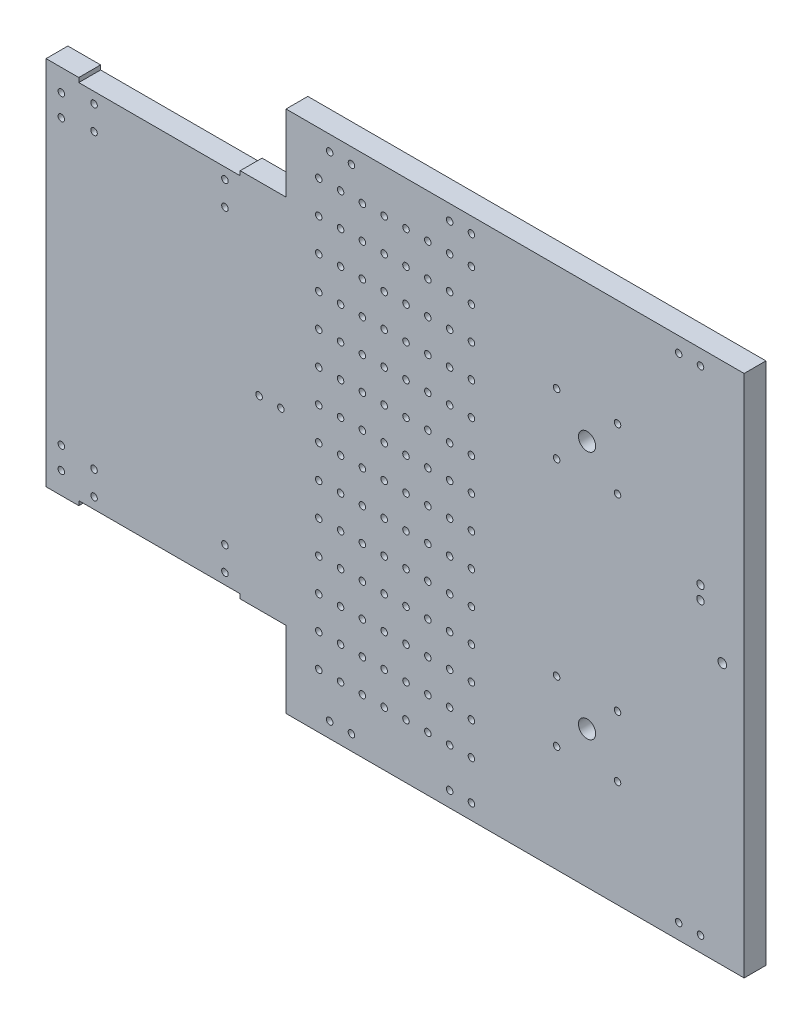
SolidWorks part; units mm, degrees
ref_plane "Front Plane" through (0, 0, 0) normal (0, 0, 1) x (1, 0, 0)
ref_plane "Top Plane" through (0, 0, 0) normal (0, 1, 0) x (1, 0, 0)
ref_plane "Right Plane" through (0, 0, 0) normal (1, 0, 0) x (0, 0, -1)
sketch "Sketch1" plane through (0, 0, 0) normal (0, 0, 1) x (1, 0, 0)
  line L0 (-89.4613, 46.5825) -> (-89.4613, 11.5825)
  line L1 (-89.4613, 46.5825) -> (120.5387, 46.5825)
  line L2 (-199.4613, 11.5825) -> (-199.4613, -158.4175)
  line L3 (-89.4613, -193.4175) -> (120.5387, -193.4175)
  line L4 (120.5387, 46.5825) -> (120.5387, -193.4175)
  line L5 (120.5387, -73.4175) -> (-199.4613, -73.4175) construction
  line L6 (-89.4613, -193.4175) -> (-89.4613, -158.4175)
  line L7 (-89.4613, 11.5825) -> (-110.4613, 11.5825)
  line L8 (-89.4613, -158.4175) -> (-110.4613, -158.4175)
  line L9 (-184.4613, 11.5825) -> (-199.4613, 11.5825)
  line L10 (-147.4667, 0.0467) -> (-147.4667, -18.5654) construction
  line L11 (-184.4613, 11.5825) -> (-184.4613, 9.5625)
  line L12 (-184.4613, 9.5625) -> (-110.4613, 9.5625)
  line L13 (-110.4613, 11.5825) -> (-110.4613, 9.5625)
  line L14 (-184.4613, -156.3975) -> (-110.4613, -156.3975)
  line L15 (-184.4613, -158.4175) -> (-184.4613, -156.3975)
  line L16 (-110.4613, -158.4175) -> (-110.4613, -156.3975)
  line L17 (15.5387, 46.5825) -> (15.5387, -193.4175) construction
  line L18 (-184.4613, -158.4175) -> (-199.4613, -158.4175)
  line L19 (31.0387, -16.339) -> (66.0387, -16.339) construction
  line L20 (31.0387, 1.1493) -> (66.0387, 1.1493) construction
  line L21 (31.0387, 1.1493) -> (31.0387, -33.8273) construction
  line L22 (31.0387, -33.8273) -> (66.0387, -33.8273) construction
  line L23 (66.0387, 1.1493) -> (66.0387, -33.8273) construction
  line L24 (31.0387, 1.1493) -> (66.0387, -33.8273) construction
  line L25 (31.0387, -33.8273) -> (66.0387, 1.1493) construction
  line L26 (48.5387, 1.1493) -> (48.5387, -33.8273) construction
  line L27 (48.5387, -147.9844) -> (48.5387, -113.0078) construction
  line L28 (31.0387, -113.0078) -> (66.0387, -147.9844) construction
  line L29 (31.0387, -147.9844) -> (66.0387, -113.0078) construction
  line L30 (66.0387, -147.9844) -> (66.0387, -113.0078) construction
  line L31 (31.0387, -113.0078) -> (66.0387, -113.0078) construction
  line L32 (31.0387, -147.9844) -> (31.0387, -113.0078) construction
  line L33 (31.0387, -147.9844) -> (66.0387, -147.9844) construction
  line L34 (31.0387, -130.4961) -> (66.0387, -130.4961) construction
  line L35 (-91.8179, -73.4175) -> (-101.8179, -73.4175) construction
  line L36 (-36.9613, 46.5825) -> (-36.9613, 37.4665) construction
  circle A0 centre (-177.4613, 4.5825) radius 1.5
  circle A1 centre (-177.4718, -6.4175) radius 1.5
  circle A2 centre (-117.472, 4.5825) radius 1.5
  circle A3 centre (-117.4616, -6.4175) radius 1.5
  circle A4 centre (-177.4718, -6.4175) radius 1.5
  circle A5 centre (-177.4613, 4.5825) radius 1.5
  circle A6 centre (-117.4616, -6.4175) radius 1.5
  circle A7 centre (-117.472, 4.5825) radius 1.5
  circle A8 centre (-177.4613, 4.5825) radius 1.5
  circle A9 centre (-177.4718, -6.4175) radius 1.5
  circle A10 centre (-117.472, 4.5825) radius 1.5
  circle A11 centre (-117.4616, -6.4175) radius 1.5
  circle A12 centre (-177.4718, -6.4175) radius 1.5
  circle A13 centre (-177.4613, 4.5825) radius 1.5
  circle A14 centre (-117.4616, -6.4175) radius 1.5
  circle A15 centre (-117.472, 4.5825) radius 1.5
  circle A16 centre (-177.4613, 4.5825) radius 1.5
  circle A17 centre (-177.4718, -6.4175) radius 1.5
  circle A18 centre (-117.472, 4.5825) radius 1.5
  circle A19 centre (-117.4616, -6.4175) radius 1.5
  circle A20 centre (-177.4718, -6.4175) radius 1.5
  circle A21 centre (-177.4613, 4.5825) radius 1.5
  circle A22 centre (-117.4616, -6.4175) radius 1.5
  circle A23 centre (-117.472, 4.5825) radius 1.5
  circle A24 centre (-177.4613, 4.5825) radius 1.5
  circle A25 centre (-177.4718, -6.4175) radius 1.5
  circle A26 centre (-117.472, 4.5825) radius 1.5
  circle A27 centre (-117.4616, -6.4175) radius 1.5
  circle A28 centre (-177.4718, -6.4175) radius 1.5
  circle A29 centre (-177.4613, 4.5825) radius 1.5
  circle A30 centre (-117.4616, -6.4175) radius 1.5
  circle A31 centre (-117.472, 4.5825) radius 1.5
  circle A32 centre (-117.472, -151.4175) radius 1.5
  circle A33 centre (-117.4616, -140.4175) radius 1.5
  circle A34 centre (-177.4718, -140.4175) radius 1.5
  circle A35 centre (-177.4613, -151.4175) radius 1.5
  circle A36 centre (48.5387, -16.339) radius 3.94
  circle A37 centre (34.5754, -2.385) radius 1.5
  circle A38 centre (62.502, -2.385) radius 1.5
  circle A39 centre (62.502, -30.293) radius 1.5
  circle A40 centre (34.5754, -30.293) radius 1.5
  circle A41 centre (34.5754, -116.5421) radius 1.5
  circle A42 centre (62.502, -116.5421) radius 1.5
  circle A43 centre (62.502, -144.4501) radius 1.5
  circle A44 centre (34.5754, -144.4501) radius 1.5
  circle A45 centre (48.5387, -130.4961) radius 3.94
  circle A46 centre (-74.4613, 26.5825) radius 1.5
  circle A47 centre (100.5387, -186.4175) radius 1.5
  circle A48 centre (90.5387, -186.4175) radius 1.5
  circle A49 centre (-59.4613, -186.4175) radius 1.5
  circle A50 centre (-69.4613, -186.4175) radius 1.5
  circle A51 centre (-69.4613, 39.5825) radius 1.5
  circle A52 centre (-59.4613, 39.5825) radius 1.5
  circle A53 centre (90.5387, 39.5825) radius 1.5
  circle A54 centre (100.5387, 39.5825) radius 1.5
  circle A55 centre (-64.4613, 26.5825) radius 1.5
  circle A56 centre (-54.4613, 26.5825) radius 1.5
  circle A57 centre (-44.4613, 26.5825) radius 1.5
  circle A58 centre (-34.4613, 26.5825) radius 1.5
  circle A59 centre (-24.4613, 26.5825) radius 1.5
  circle A60 centre (-14.4613, 26.5825) radius 1.5
  circle A61 centre (-4.4613, 26.5825) radius 1.5
  circle A62 centre (-64.4613, 11.5825) radius 1.5
  circle A63 centre (-54.4613, 11.5825) radius 1.5
  circle A64 centre (-44.4613, 11.5825) radius 1.5
  circle A65 centre (-34.4613, 11.5825) radius 1.5
  circle A66 centre (-24.4613, 11.5825) radius 1.5
  circle A67 centre (-14.4613, 11.5825) radius 1.5
  circle A68 centre (-4.4613, 11.5825) radius 1.5
  circle A69 centre (-64.4613, -3.4175) radius 1.5
  circle A70 centre (-54.4613, -3.4175) radius 1.5
  circle A71 centre (-44.4613, -3.4175) radius 1.5
  circle A72 centre (-34.4613, -3.4175) radius 1.5
  circle A73 centre (-24.4613, -3.4175) radius 1.5
  circle A74 centre (-14.4613, -3.4175) radius 1.5
  circle A75 centre (-4.4613, -3.4175) radius 1.5
  circle A76 centre (-64.4613, -18.4175) radius 1.5
  circle A77 centre (-54.4613, -18.4175) radius 1.5
  circle A78 centre (-44.4613, -18.4175) radius 1.5
  circle A79 centre (-34.4613, -18.4175) radius 1.5
  circle A80 centre (-24.4613, -18.4175) radius 1.5
  circle A81 centre (-14.4613, -18.4175) radius 1.5
  circle A82 centre (-4.4613, -18.4175) radius 1.5
  circle A83 centre (-64.4613, -33.4175) radius 1.5
  circle A84 centre (-54.4613, -33.4175) radius 1.5
  circle A85 centre (-44.4613, -33.4175) radius 1.5
  circle A86 centre (-34.4613, -33.4175) radius 1.5
  circle A87 centre (-24.4613, -33.4175) radius 1.5
  circle A88 centre (-14.4613, -33.4175) radius 1.5
  circle A89 centre (-4.4613, -33.4175) radius 1.5
  circle A90 centre (-64.4613, -48.4175) radius 1.5
  circle A91 centre (-54.4613, -48.4175) radius 1.5
  circle A92 centre (-44.4613, -48.4175) radius 1.5
  circle A93 centre (-34.4613, -48.4175) radius 1.5
  circle A94 centre (-24.4613, -48.4175) radius 1.5
  circle A95 centre (-14.4613, -48.4175) radius 1.5
  circle A96 centre (-4.4613, -48.4175) radius 1.5
  circle A97 centre (-64.4613, -63.4175) radius 1.5
  circle A98 centre (-54.4613, -63.4175) radius 1.5
  circle A99 centre (-44.4613, -63.4175) radius 1.5
  circle A100 centre (-34.4613, -63.4175) radius 1.5
  circle A101 centre (-24.4613, -63.4175) radius 1.5
  circle A102 centre (-14.4613, -63.4175) radius 1.5
  circle A103 centre (-4.4613, -63.4175) radius 1.5
  circle A104 centre (-64.4613, -78.4175) radius 1.5
  circle A105 centre (-54.4613, -78.4175) radius 1.5
  circle A106 centre (-44.4613, -78.4175) radius 1.5
  circle A107 centre (-34.4613, -78.4175) radius 1.5
  circle A108 centre (-24.4613, -78.4175) radius 1.5
  circle A109 centre (-14.4613, -78.4175) radius 1.5
  circle A110 centre (-4.4613, -78.4175) radius 1.5
  circle A111 centre (-64.4613, -93.4175) radius 1.5
  circle A112 centre (-54.4613, -93.4175) radius 1.5
  circle A113 centre (-44.4613, -93.4175) radius 1.5
  circle A114 centre (-34.4613, -93.4175) radius 1.5
  circle A115 centre (-24.4613, -93.4175) radius 1.5
  circle A116 centre (-14.4613, -93.4175) radius 1.5
  circle A117 centre (-4.4613, -93.4175) radius 1.5
  circle A118 centre (-64.4613, -108.4175) radius 1.5
  circle A119 centre (-54.4613, -108.4175) radius 1.5
  circle A120 centre (-44.4613, -108.4175) radius 1.5
  circle A121 centre (-34.4613, -108.4175) radius 1.5
  circle A122 centre (-24.4613, -108.4175) radius 1.5
  circle A123 centre (-14.4613, -108.4175) radius 1.5
  circle A124 centre (-4.4613, -108.4175) radius 1.5
  circle A125 centre (-64.4613, -123.4175) radius 1.5
  circle A126 centre (-54.4613, -123.4175) radius 1.5
  circle A127 centre (-44.4613, -123.4175) radius 1.5
  circle A128 centre (-34.4613, -123.4175) radius 1.5
  circle A129 centre (-24.4613, -123.4175) radius 1.5
  circle A130 centre (-14.4613, -123.4175) radius 1.5
  circle A131 centre (-4.4613, -123.4175) radius 1.5
  circle A132 centre (-64.4613, -138.4175) radius 1.5
  circle A133 centre (-54.4613, -138.4175) radius 1.5
  circle A134 centre (-44.4613, -138.4175) radius 1.5
  circle A135 centre (-34.4613, -138.4175) radius 1.5
  circle A136 centre (-24.4613, -138.4175) radius 1.5
  circle A137 centre (-14.4613, -138.4175) radius 1.5
  circle A138 centre (-4.4613, -138.4175) radius 1.5
  circle A139 centre (-64.4613, -153.4175) radius 1.5
  circle A140 centre (-54.4613, -153.4175) radius 1.5
  circle A141 centre (-44.4613, -153.4175) radius 1.5
  circle A142 centre (-34.4613, -153.4175) radius 1.5
  circle A143 centre (-24.4613, -153.4175) radius 1.5
  circle A144 centre (-14.4613, -153.4175) radius 1.5
  circle A145 centre (-4.4613, -153.4175) radius 1.5
  circle A146 centre (-74.4613, 11.5825) radius 1.5
  circle A147 centre (-74.4613, -3.4175) radius 1.5
  circle A148 centre (-74.4613, -18.4175) radius 1.5
  circle A149 centre (-74.4613, -33.4175) radius 1.5
  circle A150 centre (-74.4613, -48.4175) radius 1.5
  circle A151 centre (-74.4613, -63.4175) radius 1.5
  circle A152 centre (-74.4613, -78.4175) radius 1.5
  circle A153 centre (-74.4613, -93.4175) radius 1.5
  circle A154 centre (-74.4613, -108.4175) radius 1.5
  circle A155 centre (-74.4613, -123.4175) radius 1.5
  circle A156 centre (-74.4613, -138.4175) radius 1.5
  circle A157 centre (-74.4613, -153.4175) radius 1.5
  circle A158 centre (-192.4613, -8.4175) radius 1.5
  circle A159 centre (-192.4613, 1.5825) radius 1.5
  circle A160 centre (-192.4613, -148.4175) radius 1.5
  circle A161 centre (-192.4613, -138.4175) radius 1.5
  circle A162 centre (-101.8179, -73.4175) radius 1.5
  circle A163 centre (-91.8179, -73.4175) radius 1.5
  circle A164 centre (-4.4613, -186.4175) radius 1.5
  circle A165 centre (-14.4613, -186.4175) radius 1.5
  circle A166 centre (-14.4613, 39.5825) radius 1.5
  circle A167 centre (-4.4613, 39.5825) radius 1.5
  circle A168 centre (-74.4613, -168.4175) radius 1.5
  circle A169 centre (-64.4613, -168.4175) radius 1.5
  circle A170 centre (-54.4613, -168.4175) radius 1.5
  circle A171 centre (-44.4613, -168.4175) radius 1.5
  circle A172 centre (-34.4613, -168.4175) radius 1.5
  circle A173 centre (-24.4613, -168.4175) radius 1.5
  circle A174 centre (-14.4613, -168.4175) radius 1.5
  circle A175 centre (-4.4613, -168.4175) radius 1.5
  circle A176 centre (100.5387, -53.4175) radius 1.7007
  circle A177 centre (100.5387, -47.3175) radius 1.7
  circle A178 centre (110.5387, -73.4175) radius 2
  point P71 (48.5387, -16.339)
  dimension "D10" = 3
  dimension "D11" = 3
  dimension "D14" = 7.88
  dimension "D19" = 3
  dimension "D20" = 3
  dimension "D24" = 8
  dimension "D26" = 35
  dimension "D28" = 20
  dimension "D8" = 15
  dimension "D4" = 3
  dimension "D17" = 3
  dimension "D36" = 3.4014
  dimension "D29" = 3.4
  dimension "D38" = 10
  dimension "D39" = 4
  dimension "D1" = 320
  dimension "D2" = 240
  dimension "D3" = 110
  dimension "D5" = 2.02
  dimension "D6" = 74
  dimension "D7" = 15
  dimension "D9" = 7
  dimension "D12" = 11
  dimension "D13" = 20
  dimension "D15" = 72
  dimension "D16" = 35
  dimension "D18" = 5
  dimension "D21" = 10
  dimension "D25" = 14
  dimension "D30" = 6.1
  dimension "D22" = 20
  dimension "D23" = 7
  dimension "D27" = 10
  dimension "D31" = 10
  dimension "D32" = 7
  dimension "D33" = 10
  dimension "D34" = 7
  dimension "D35" = 52.5
  dimension "D37" = 20
extrude "Boss-Extrude1" add sketch "Sketch1" along normal blind 10
